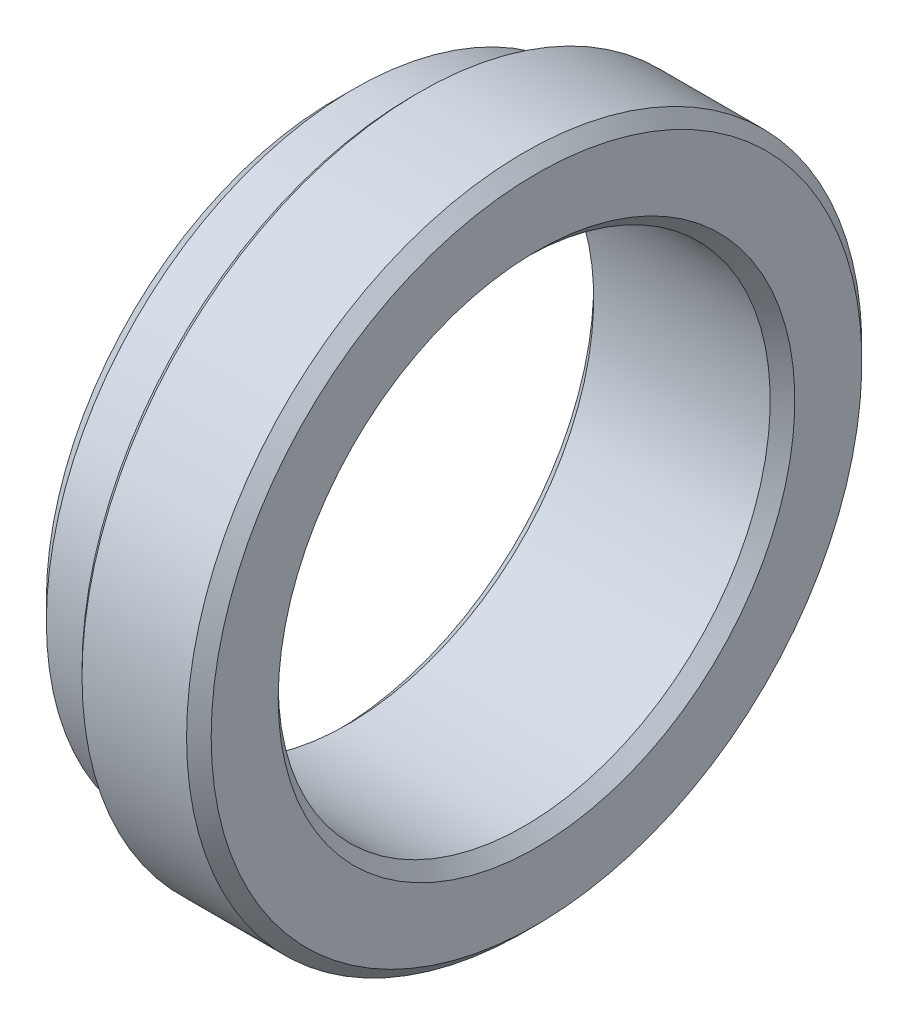
SolidWorks part; units mm, degrees
ref_plane "Alzado" through (0, 0, 0) normal (0, 0, 1) x (1, 0, 0)
ref_plane "Planta" through (0, 0, 0) normal (0, 1, 0) x (1, 0, 0)
ref_plane "Vista lateral" through (0, 0, 0) normal (1, 0, 0) x (0, 0, -1)
sketch "Croquis2" plane through (0, 0, 0) normal (0, 0, 1) x (1, 0, 0)
  line L0 (0, 0) -> (42.6287, 0) construction
  line L1 (0, 23.5) -> (0, 21)
  line L2 (1, 20) -> (15.35, 20)
  line L3 (16.35, 21) -> (16.35, 26.45)
  line L4 (15.35, 27.45) -> (6.85, 27.45)
  line L5 (6.35, 26.95) -> (6.35, 25)
  line L6 (5.35, 25) -> (1.5, 25)
  line L7 (0, 21) -> (1, 20)
  line L8 (15.35, 20) -> (16.35, 21)
  line L9 (1.5, 25) -> (0, 23.5)
  line L10 (16.35, 26.45) -> (15.35, 27.45)
  line L11 (6.85, 27.45) -> (6.35, 26.95)
  arc A0 (5.35, 25) -> (6.35, 25) centre (5.85, 25) ccw
  point P3 (0, 25)
  point P4 (0, 20)
  point P6 (16.35, 20)
  point P7 (16.35, 27.45)
  point P10 (6.35, 27.45)
  dimension "D6" = 1
  dimension "D1" = 20
  dimension "D2" = 54.9
  dimension "D3" = 25
  dimension "D4" = 10
  dimension "D5" = 6.35
  dimension "D7" = 1.5
revolve "Revolución1" add sketch "Croquis2" angle 360 about L0
